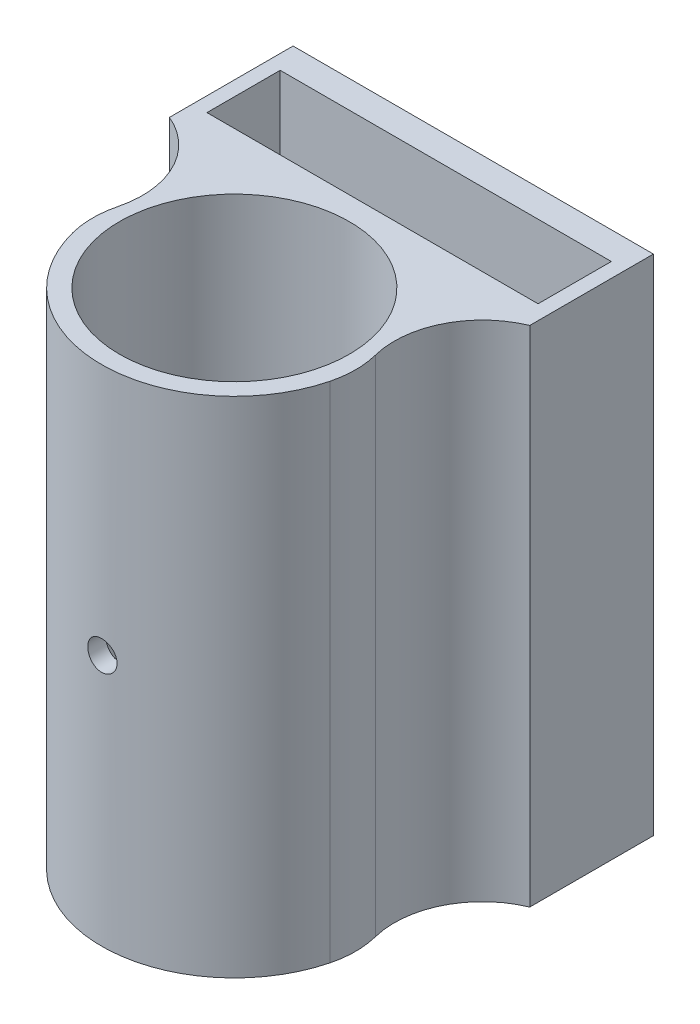
SolidWorks part; units mm, degrees
ref_plane "Front Plane" through (0, 0, 0) normal (0, 0, 1) x (1, 0, 0)
ref_plane "Top Plane" through (0, 0, 0) normal (0, 1, 0) x (1, 0, 0)
ref_plane "Right Plane" through (0, 0, 0) normal (1, 0, 0) x (0, 0, -1)
sketch "Sketch4" plane through (0, 0, 0) normal (0, 1, 0) x (1, 0, 0)
  line L1 (-19.6718, 26.0785) -> (19.6718, 26.0785)
  line L2 (19.6718, 26.0785) -> (19.6718, 12.5785)
  line L3 (-19.6718, 26.0785) -> (-19.6718, 12.5785)
  arc A0 (14.5, 0) -> (-14.5, 0) centre (0, 0) cw
  circle A5 centre (0, 0) radius 12.5
  arc A6 (14.5, 0) -> (19.6718, 12.5785) centre (23.3752, 3.7033) cw
  arc A7 (-14.5, 0) -> (-19.6718, 12.5785) centre (-23.3752, 3.7033) ccw
  dimension "D1" = 13.5
extrude "Boss-Extrude2" add sketch "Sketch4" along normal blind 55
sketch "Sketch7" plane through (0, 0, 0) normal (0, 1, 0) x (1, 0, 0)
  circle A0 centre (0, 0) radius 12.55
extrude "Cut-Extrude2" cut sketch "Sketch7" along normal through all
sketch "Sketch8" plane through (0, 0, -26.0785) normal (0, 0, -1) x (-1, 0, 0)
  line L0 (19.6718, 55) -> (-19.6718, 55) construction
  circle A0 centre (0, 27.5) radius 1.6
  dimension "D1" = 27.5
extrude "Cut-Extrude3" cut sketch "Sketch8" against normal through all
sketch "Sketch10" plane through (0, 0, -26.0785) normal (0, 0, -1) x (-1, 0, 0)
  line L0 (0, 27.5) -> (19.6718, 27.5)
  line L1 (19.6718, 55) -> (19.6718, 0) construction
  circle A0 centre (8.8388, 36.3388) radius 1.6
  circle A1 centre (8.8388, 18.6612) radius 1.6
  circle A2 centre (-8.8388, 18.6612) radius 1.6
  circle A3 centre (-8.8388, 36.3388) radius 1.6
  point P16 (0, 27.5)
  dimension "D1" = 12.5
  dimension "D2" = 4
extrude "Cut-Extrude5" cut sketch "Sketch10" against normal blind 8 contours A1 | A0 | A3 | A2
sketch "Sketch11" plane through (0, 55, 0) normal (0, 1, 0) x (1, 0, 0)
  line L0 (-19.6718, 26.0785) -> (19.6718, 26.0785) construction
  line L1 (-18.0777, 15.0785) -> (18.0777, 15.0785)
  line L2 (-18.0777, 15.0785) -> (-18.0777, 23.0785)
  line L3 (-18.0777, 23.0785) -> (18.0777, 23.0785)
  line L4 (18.0777, 15.0785) -> (18.0777, 23.0785)
  line L5 (-18.0777, 15.0785) -> (18.0777, 23.0785) construction
  line L6 (-18.0777, 23.0785) -> (18.0777, 15.0785) construction
  point P0 (0, 19.0785)
  dimension "D1" = 3
  dimension "D2" = 36.1554
  dimension "D3" = 8
extrude "Cut-Extrude6" cut sketch "Sketch11" against normal through all
fillet "Fillet1" radius 10 2 edges at (14.5, 27.5, 0) (-14.5, 27.5, 0)
